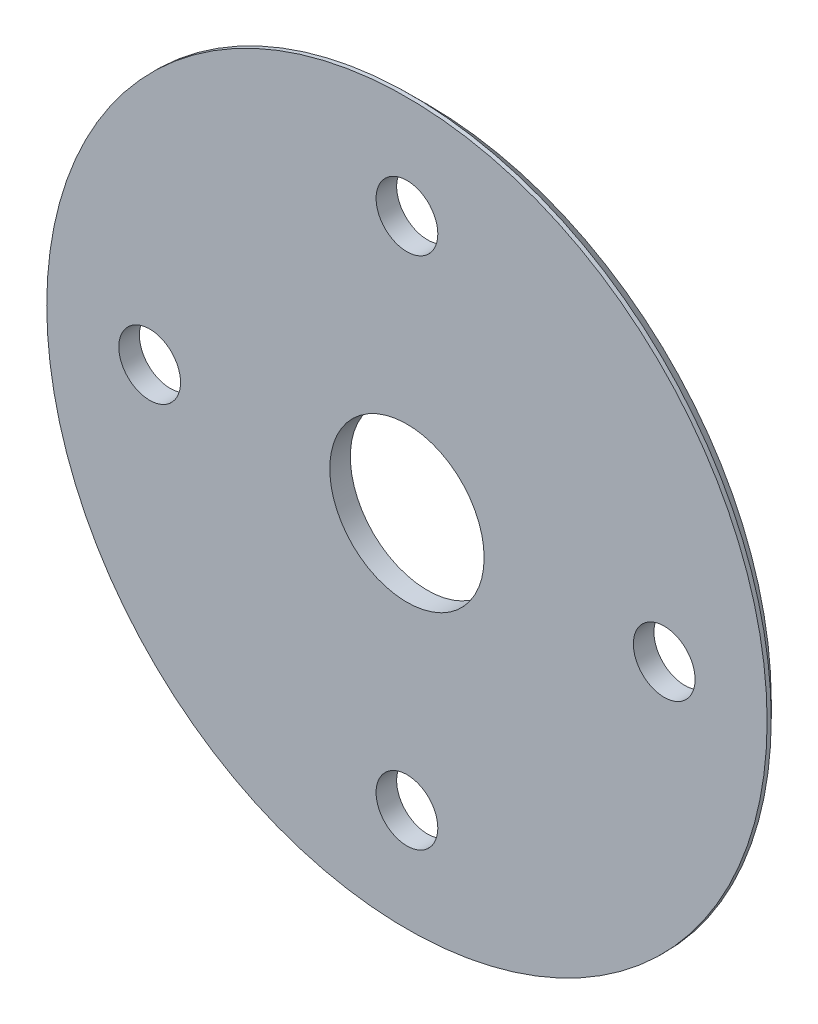
SolidWorks part; units mm, degrees
ref_plane "Front Plane" through (0, 0, 0) normal (0, 0, 1) x (1, 0, 0)
ref_plane "Top Plane" through (0, 0, 0) normal (0, 1, 0) x (1, 0, 0)
ref_plane "Right Plane" through (0, 0, 0) normal (1, 0, 0) x (0, 0, -1)
sketch "Sketch1" plane through (0, 0, 0) normal (0, 0, 1) x (1, 0, 0)
  circle A0 centre (0, 0) radius 35
  circle A1 centre (0, 0) radius 7.5
  circle A2 centre (25, 0) radius 3
  circle A3 centre (0, -25) radius 3
  circle A4 centre (-25, 0) radius 3
  circle A5 centre (0, 25) radius 3
  point P15 (0, 0)
  dimension "D1" = 70
  dimension "D2" = 6
  dimension "D3" = 15
  dimension "D4" = 25
  dimension "D5" = 4
extrude "Boss-Extrude1" add sketch "Sketch1" along normal blind 2
chamfer "Chamfer1" distance 1.6 angle 45 1 edges at (35, 0, 0)
